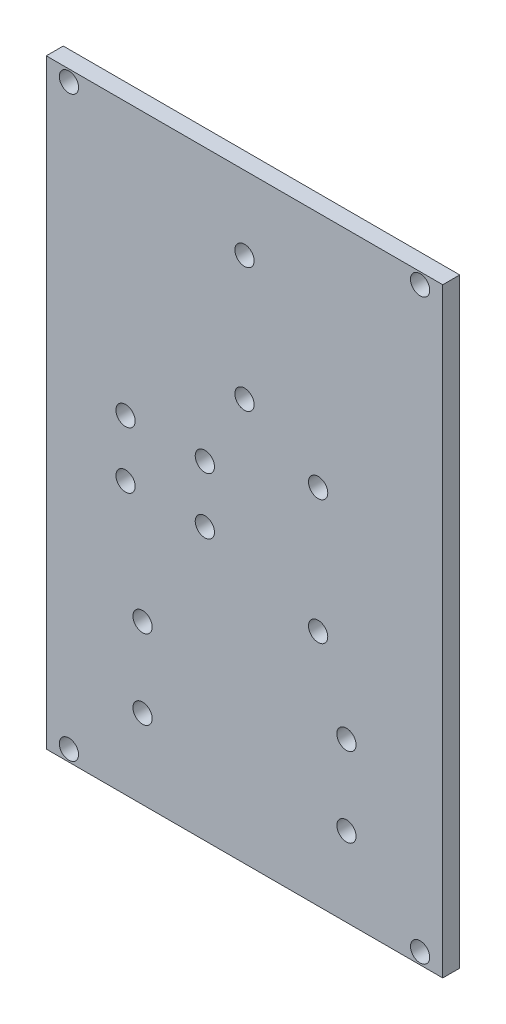
SolidWorks part; units mm, degrees
other "Power Electronics Shelf"
ref_plane "Front Plane" through (0, 0, 0) normal (0, 0, 1) x (1, 0, 0)
ref_plane "Top Plane" through (0, 0, 0) normal (0, 1, 0) x (1, 0, 0)
ref_plane "Right Plane" through (0, 0, 0) normal (1, 0, 0) x (0, 0, -1)
sketch3d "Main Profile Sketch datum points"
  point P0 (0, 0, 88)
  point P1 (10, 0, 88)
  point P2 (0, 10, 88)
ref_plane "Main Profile Sketch plane" through (0, 0, 88) normal (0, 0, 1) x (1, 0, 0)
sketch "Main Profile Sketch" plane through (0, 0, 88) normal (0, 0, 1) x (1, 0, 0)
  line L0 (-238, 53) -> (-168, 53)
  line L1 (-168, 53) -> (-168, -53)
  line L2 (-238, -53) -> (-168, -53)
  line L3 (-238, 53) -> (-238, -53)
  circle A0 centre (-234, -51) radius 1.7
  circle A1 centre (-221, -39) radius 1.7
  circle A2 centre (-221, -25) radius 1.7
  circle A3 centre (-224, -5) radius 1.7
  circle A4 centre (-210, -5) radius 1.7
  circle A5 centre (-172, -51) radius 1.7
  circle A6 centre (-185, -39) radius 1.7
  circle A7 centre (-190, -11) radius 1.7
  circle A8 centre (-185, -25) radius 1.7
  circle A9 centre (-224, 5) radius 1.7
  circle A10 centre (-210, 5) radius 1.7
  circle A11 centre (-234, 51) radius 1.7
  circle A12 centre (-190, 11) radius 1.7
  circle A13 centre (-203, 18) radius 1.7
  circle A14 centre (-203, 40) radius 1.7
  circle A15 centre (-172, 51) radius 1.7
extrude "Main Extrusion" add sketch "Main Profile Sketch" against normal blind 3 separate body
